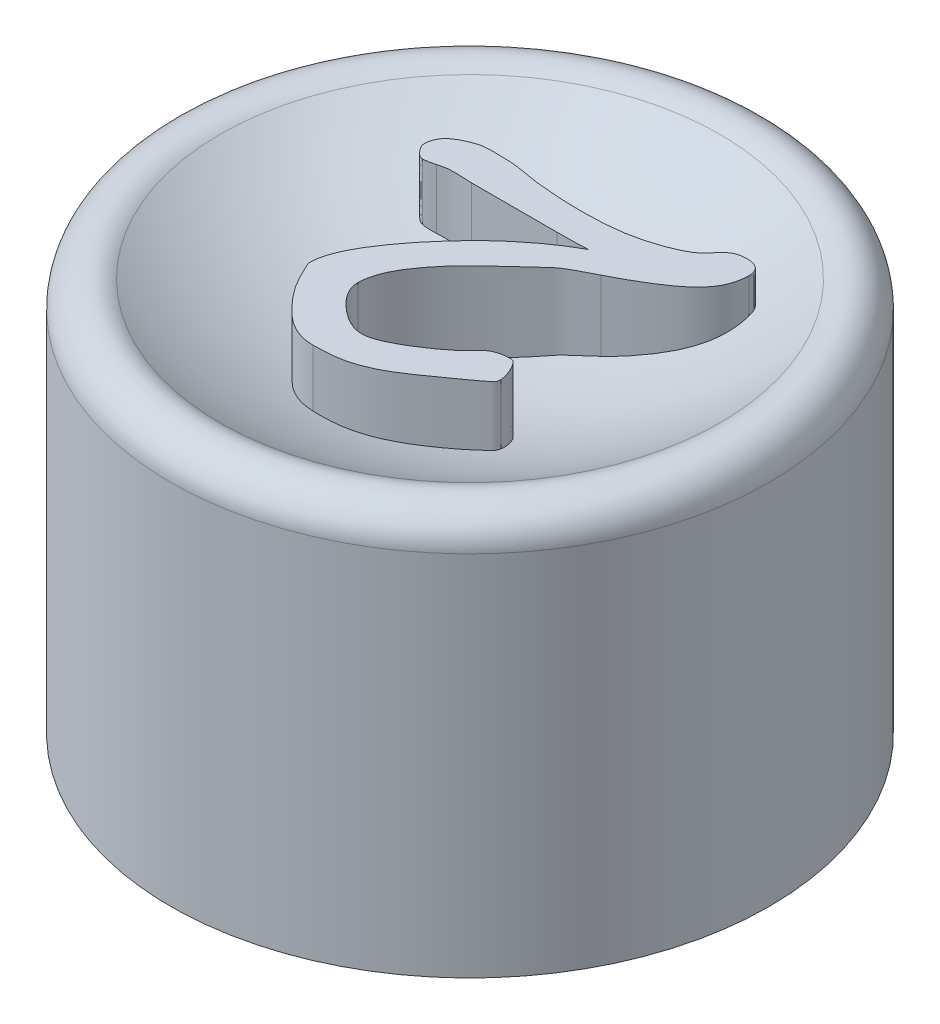
SolidWorks part; units mm, degrees
ref_plane "Front Plane" through (0, 0, 0) normal (0, 0, 1) x (1, 0, 0)
ref_plane "Top Plane" through (0, 0, 0) normal (0, 1, 0) x (1, 0, 0)
ref_plane "Right Plane" through (0, 0, 0) normal (1, 0, 0) x (0, 0, -1)
sketch "Sketch1" plane through (0, 0, 0) normal (0, 0, 1) x (1, 0, 0)
  line L0 (0, 0) -> (0, -66.4851) construction
  line L1 (55, 0) -> (-55, 0) construction
  line L2 (-1.5494, 0) -> (-1.5494, 3.048)
  line L3 (-1.5494, 3.048) -> (-0.762, 3.048)
  line L4 (-0.762, 3.048) -> (-0.762, 4.064)
  line L5 (-0.762, 4.064) -> (0, 4.064)
  line L6 (0, -55) -> (0, 55) construction
  line L7 (0, 4.064) -> (0, 5.08)
  line L8 (-4.7625, 5.842) -> (-4.7625, 0)
  line L9 (-4.7625, 0) -> (-3.4925, 0)
  line L10 (-3.4925, 0) -> (-3.4925, 4.064)
  line L11 (-3.4925, 4.064) -> (-2.0574, 4.064)
  line L12 (-2.0574, 4.064) -> (-2.0574, 0)
  line L13 (-2.0574, 0) -> (-1.5494, 0)
  line L14 (0, 5.08) -> (3.3062, 5.08) construction
  arc A0 (-4.7625, 5.842) -> (-3.976, 6.2669) centre (-4.2545, 5.842) cw
  arc A1 (-3.976, 6.2669) -> (0, 5.08) centre (0, 12.3333) ccw
  dimension "D4" = 1.524
  dimension "D5" = 6.35
  dimension "D9" = 0.508
  dimension "D1" = 9.525
  dimension "D2" = 3.0988
  dimension "D3" = 3.048
  dimension "D6" = 0.508
  dimension "D7" = 1.016
  dimension "D8" = 1.27
  dimension "D10" = 5.08
revolve "Revolve1" add sketch "Sketch1" angle 360 about L0
ref_plane "Plane1" through (0, 6.35, 0) normal (0, 1, 0) x (-1, 0, 0)
sketch "Sketch3" plane through (0, 6.35, 0) normal (0, 1, 0) x (-1, 0, 0)
  line L0 (-2.3812, -2.032) -> (2.3813, -2.032) construction
  line L1 (0, 0) -> (0, -7.9672) construction
  line L2 (0, 3.4925) -> (0, -3.4925) construction
  line L3 (3.4925, 0) -> (-3.4925, 0) construction
  text T0 "2" font "Segoe Print" height 4.7625
  dimension "D1" = 2.032
  dimension "D2" = 4.7625
extrude "Boss-Extrude1" add sketch "Sketch3" against normal up to surface (0.9082 mm away)
